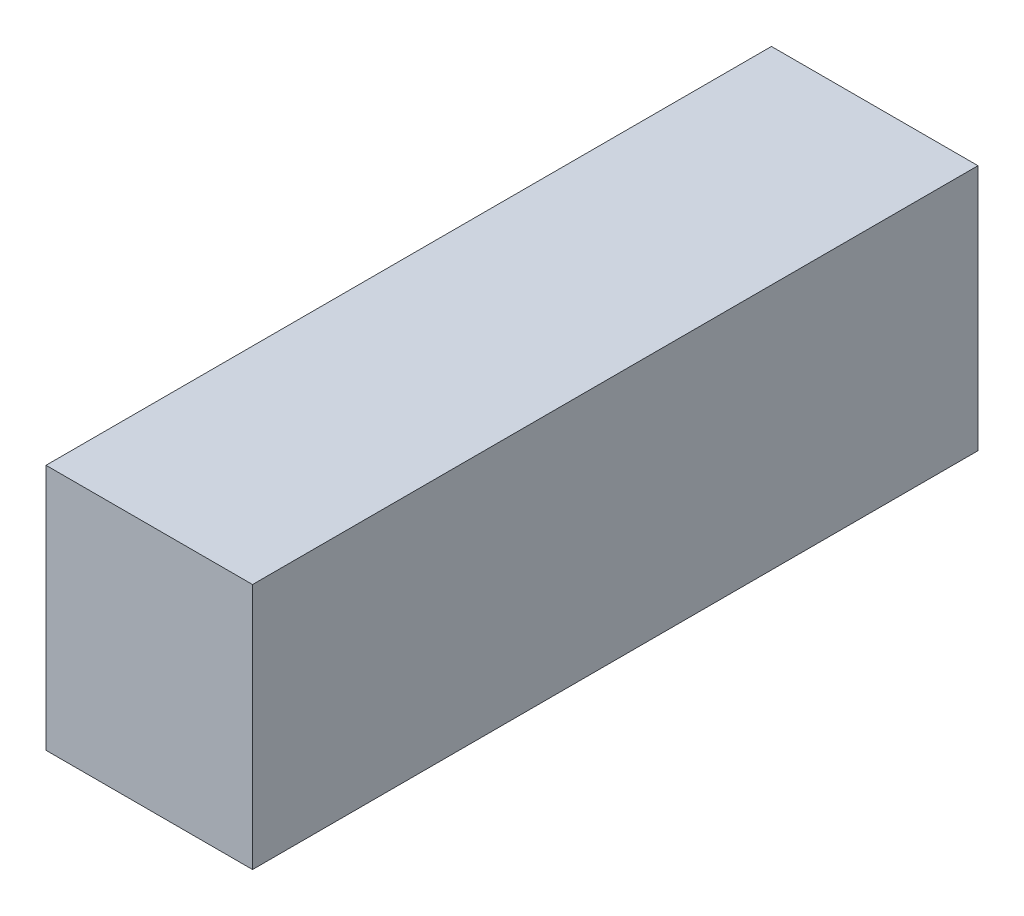
SolidWorks part; units mm, degrees
ref_plane "Front Plane" through (0, 0, 0) normal (0, 0, 1) x (1, 0, 0)
ref_plane "Top Plane" through (0, 0, 0) normal (0, 1, 0) x (1, 0, 0)
ref_plane "Right Plane" through (0, 0, 0) normal (1, 0, 0) x (0, 0, -1)
sketch "Sketch1" plane through (0, 0, 0) normal (0, 1, 0) x (1, 0, 0)
  line L1 (-20.5, 72) -> (20.5, 72)
  line L2 (-20.5, 72) -> (-20.5, -72)
  line L3 (-20.5, -72) -> (20.5, -72)
  line L4 (20.5, 72) -> (20.5, -72)
  line L5 (-20.5, 72) -> (20.5, -72) construction
  line L6 (-20.5, -72) -> (20.5, 72) construction
  point P0 (0, 0)
  dimension "D1" = 144
  dimension "D2" = 41
extrude "Boss-Extrude1" add sketch "Sketch1" along normal blind 49
